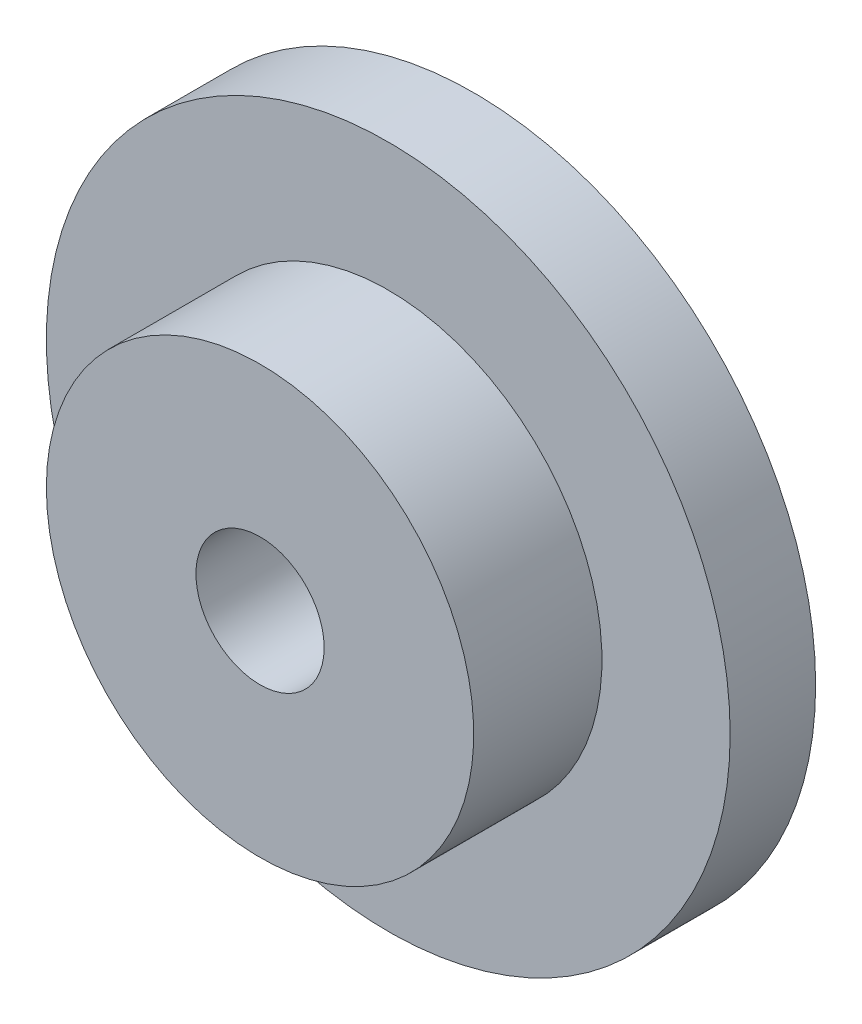
SolidWorks part; units mm, degrees
ref_plane "Front Plane" through (0, 0, 0) normal (0, 0, 1) x (1, 0, 0)
ref_plane "Top Plane" through (0, 0, 0) normal (0, 1, 0) x (1, 0, 0)
ref_plane "Right Plane" through (0, 0, 0) normal (1, 0, 0) x (0, 0, -1)
sketch "Sketch1" plane through (0, 0, 0) normal (0, 0, 1) x (1, 0, 0)
  circle A0 centre (0, 0) radius 25.4
  dimension "D1" = 50.8
extrude "Boss-Extrude1" add sketch "Sketch1" along normal blind 6.35
sketch "Sketch2" plane through (0, 0, 6.35) normal (0, 0, 1) x (1, 0, 0)
  circle A0 centre (0, 0) radius 15.875
  dimension "D1" = 31.75
extrude "Boss-Extrude2" add sketch "Sketch2" along normal blind 9.525
sketch "Sketch3" plane through (0, 0, 15.875) normal (0, 0, 1) x (1, 0, 0)
  circle A0 centre (0, 0) radius 4.7625
  dimension "D1" = 9.525
extrude "Cut-Extrude1" cut sketch "Sketch3" against normal up to surface (15.875 mm away) up to face at (25.4, 0, 0)
